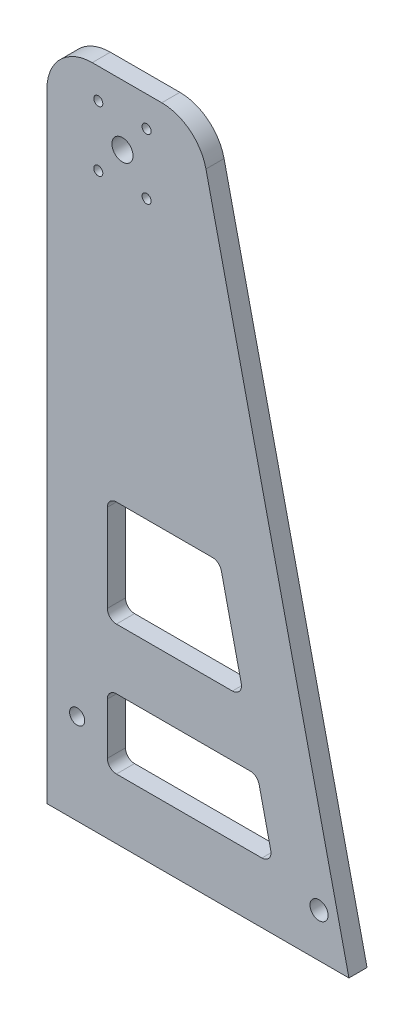
SolidWorks part; units mm, degrees
ref_plane "Plano frontal" through (0, 0, 0) normal (0, 0, 1) x (1, 0, 0)
ref_plane "Plano superior" through (0, 0, 0) normal (0, 1, 0) x (1, 0, 0)
ref_plane "Plano direito" through (0, 0, 0) normal (1, 0, 0) x (0, 0, -1)
sketch "Esboço1" plane through (0, 0, 0) normal (0, 0, 1) x (1, 0, 0)
  line L0 (0, 0) -> (0, 220)
  line L2 (100, 0) -> (0, 0)
  line L3 (0, 220) -> (50, 220)
  line L4 (50, 220) -> (100, 0)
  line L5 (10, 103) -> (10, 15) construction
  line L6 (25, 220) -> (25, 180) construction
  line L7 (10, 15) -> (75.8194, 15) construction
  line L8 (75.8194, 15) -> (55.8194, 103) construction
  line L9 (55.8194, 103) -> (10, 103) construction
  line L10 (20, 95) -> (20, 66)
  line L11 (23, 63) -> (61.4135, 63)
  line L12 (64.3389, 66.6649) -> (57.748, 95.6649)
  line L13 (54.8226, 98) -> (23, 98)
  line L14 (20, 40) -> (20, 23)
  line L15 (23, 20) -> (71.1862, 20)
  line L16 (74.1116, 23.6649) -> (70.248, 40.6649)
  line L17 (23, 43) -> (67.3226, 43)
  line L18 (17, 200) -> (33, 200) construction
  line L19 (17, 210) -> (33, 210) construction
  line L20 (17, 210) -> (17, 190) construction
  line L21 (17, 190) -> (33, 190) construction
  line L22 (33, 210) -> (33, 190) construction
  line L23 (17, 210) -> (33, 190) construction
  line L24 (17, 190) -> (33, 210) construction
  arc A8 (70.248, 40.6649) -> (67.3226, 43) centre (67.3226, 40) ccw
  arc A9 (71.1862, 20) -> (74.1116, 23.6649) centre (71.1862, 23) ccw
  arc A10 (20, 23) -> (23, 20) centre (23, 23) ccw
  arc A11 (20, 40) -> (23, 43) centre (23, 40) cw
  arc A12 (57.748, 95.6649) -> (54.8226, 98) centre (54.8226, 95) ccw
  arc A13 (61.4135, 63) -> (64.3389, 66.6649) centre (61.4135, 66) ccw
  arc A14 (20, 66) -> (23, 63) centre (23, 66) ccw
  arc A15 (20, 95) -> (23, 98) centre (23, 95) cw
  circle A16 centre (17, 210) radius 1.5
  circle A17 centre (33, 210) radius 1.5
  circle A18 centre (33, 190) radius 1.5
  circle A19 centre (17, 190) radius 1.5
  circle A20 centre (25, 200) radius 3.5
  circle A21 centre (10, 30) radius 2.5
  point P8 (25, 200)
  point P49 (20, 63)
  dimension "D3" = 20
  dimension "D4" = 16
  dimension "D6" = 3
  dimension "D7" = 7
  dimension "D21" = 3
  dimension "D20" = 10
  dimension "D22" = 5
  dimension "D1" = 220
  dimension "D2" = 100
  dimension "D5" = 50
  dimension "D9" = 20
  dimension "D10" = 20
  dimension "D11" = 10
  dimension "D12" = 20
  dimension "D13" = 15
  dimension "D14" = 20
  dimension "D15" = 10
  dimension "D16" = 29
  dimension "D17" = 17
  dimension "D18" = 10
  dimension "D19" = 30
  dimension "D8" = 20
extrude "Ressalto-extrusão2" add sketch "Esboço1" along normal blind 6
fillet "Filete1" radius 15 2 edges at (0, 220, 3) (50, 220, 3)
sketch "Esboço2" plane through (0, 0, 0) normal (0, 0, -1) x (-1, 0, 0)
  circle A0 centre (-90.0963, 14.5) radius 3
extrude "Corte-extrusão1" cut sketch "Esboço2" against normal blind 10
